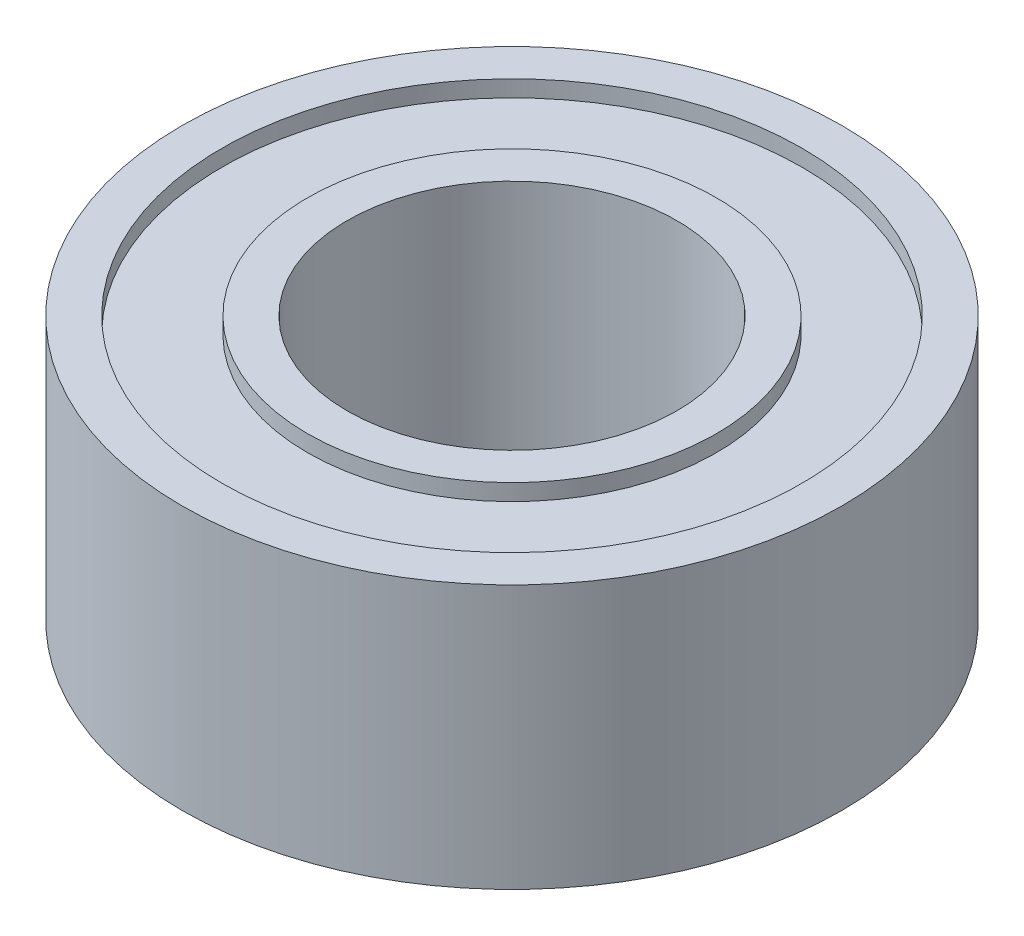
SolidWorks part; units mm, degrees
ref_plane "Front Plane" through (0, 0, 0) normal (0, 0, 1) x (1, 0, 0)
ref_plane "Top Plane" through (0, 0, 0) normal (0, 1, 0) x (1, 0, 0)
ref_plane "Right Plane" through (0, 0, 0) normal (1, 0, 0) x (0, 0, -1)
sketch "Sketch1" plane through (0, 0, 0) normal (0, 1, 0) x (1, 0, 0)
  circle A0 centre (0, 0) radius 5
  circle A1 centre (0, 0) radius 2.5
  dimension "D1" = 10
  dimension "D2" = 5
extrude "Boss-Extrude1" add sketch "Sketch1" along normal mid plane 4
sketch "Sketch2" plane through (0, 2, 0) normal (0, 1, 0) x (1, 0, 0)
  line L0 (0, 5) -> (0, 4.4) construction
  line L1 (0, 3.1) -> (0, 2.5) construction
  circle A0 centre (0, 0) radius 4.4
  circle A1 centre (0, 0) radius 3.1
  circle A2 centre (0, 0) radius 5 construction
  circle A3 centre (0, 0) radius 2.5 construction
  dimension "D1" = 0.6
extrude "Cut-Extrude1" cut sketch "Sketch2" against normal blind 0.25
mirror "Mirror1" about plane through (0, 0, 0) normal (0, 1, 0) of "Cut-Extrude1"
